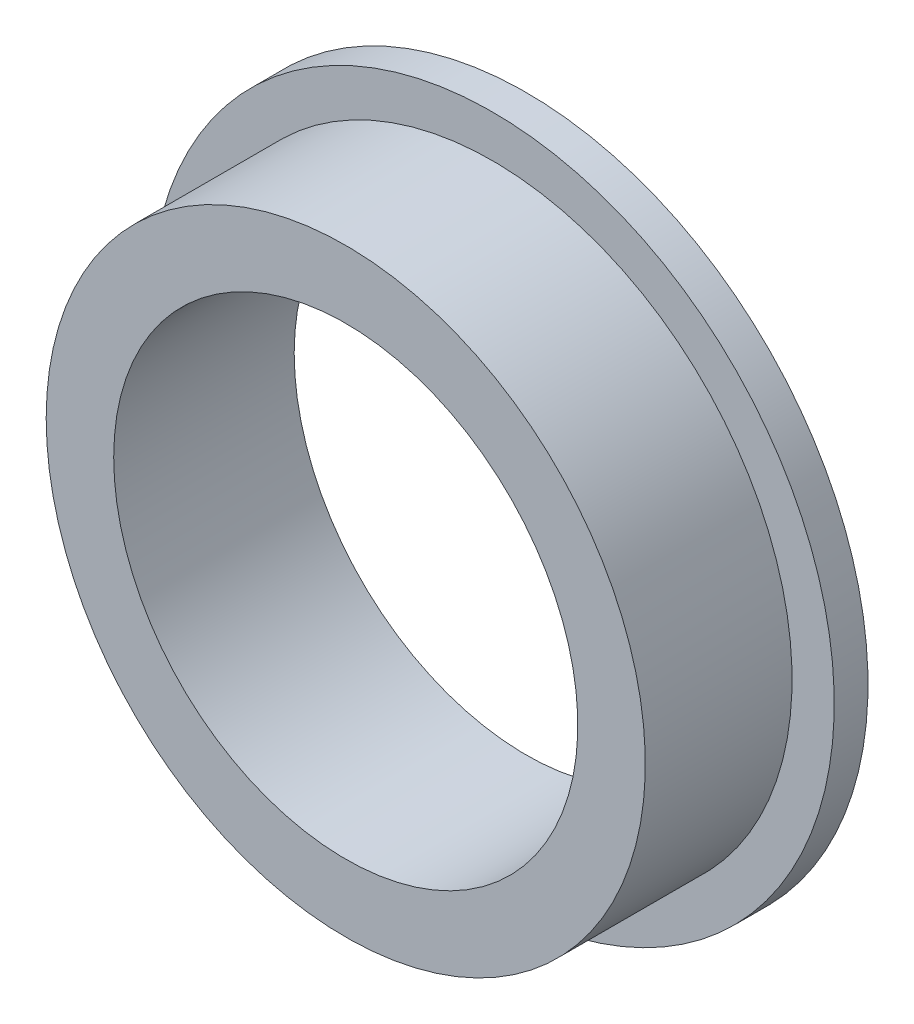
SolidWorks part; units mm, degrees
ref_plane "Front Plane" through (0, 0, 0) normal (0, 0, 1) x (1, 0, 0)
ref_plane "Top Plane" through (0, 0, 0) normal (0, 1, 0) x (1, 0, 0)
ref_plane "Right Plane" through (0, 0, 0) normal (1, 0, 0) x (0, 0, -1)
sketch "Sketch1" plane through (0, 0, 0) normal (0, 1, 0) x (1, 0, 0)
  line L0 (-27.5, 30.6236) -> (-27.5, 13.2355)
  line L1 (-27.5, 13.2355) -> (-35.5, 13.2355)
  line L2 (-35.5, 13.2355) -> (-35.5, 30.6236)
  line L3 (-35.5, 30.6236) -> (-40.5, 30.6236)
  line L4 (-40.5, 30.6236) -> (-40.5, 34.6236)
  line L5 (-40.5, 34.6236) -> (-27.5, 34.6236)
  line L6 (-27.5, 34.6236) -> (-27.5, 30.6236)
  line L7 (0, 62.8427) -> (0, -24.0978) construction
  dimension "D1" = 27.5
  dimension "D2" = 8
  dimension "D3" = 5
  dimension "D4" = 4
revolve "Revolve1" add sketch "Sketch1" angle 360 about L7
